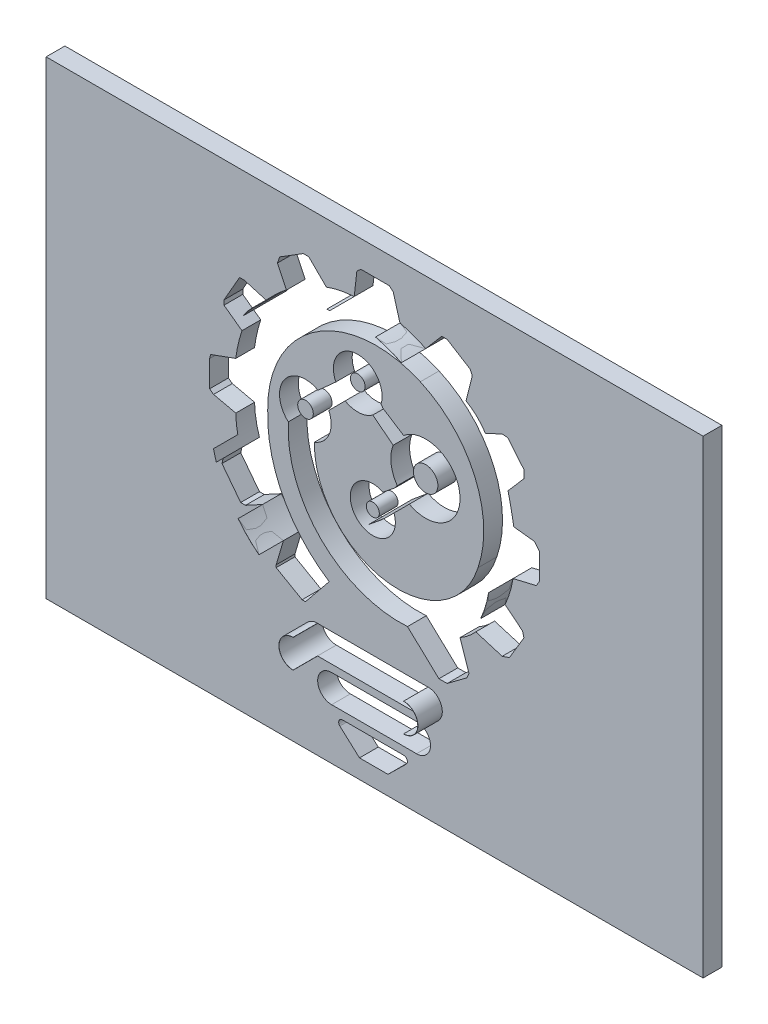
SolidWorks part; units mm, degrees
ref_plane "Front Plane" through (0, 0, 0) normal (0, 0, 1) x (1, 0, 0)
ref_plane "Top Plane" through (0, 0, 0) normal (0, 1, 0) x (1, 0, 0)
ref_plane "Right Plane" through (0, 0, 0) normal (1, 0, 0) x (0, 0, -1)
sketch "Sketch1" plane through (0, 0, 0) normal (0, 0, 1) x (1, 0, 0)
  line L0 (30.4571, 56.7891) -> (92.9051, 56.7891) construction
  line L1 (36.6127, 46.336) -> (66.0639, 46.336) construction
  line L8 (36.6127, 50.1281) -> (66.0639, 50.1281)
  line L11 (36.6127, 42.5438) -> (66.0639, 42.5438)
  line L12 (40.3711, 36.92) -> (62.9922, 36.92) construction
  line L15 (40.3711, 40.6319) -> (62.9922, 40.6319)
  line L16 (40.3711, 33.2082) -> (62.9922, 33.2082)
  line L17 (43.2916, 31.1455) -> (59.5488, 31.1455)
  line L20 (47.7936, 24.6426) -> (55.3803, 24.6426)
  line L21 (60.2553, 29.4313) -> (55.3803, 24.6426)
  line L22 (42.5548, 29.3665) -> (47.7936, 24.6426)
  line L23 (54.0424, 89.0572) -> (57.3383, 91.7453)
  line L24 (56.7754, 86.2384) -> (60.0907, 88.9424)
  line L25 (61.0672, 89.823) -> (60.0907, 88.9424)
  line L26 (57.8581, 92.482) -> (57.3383, 91.7453)
  line L27 (56.7753, 101.2636) -> (51.3382, 105.5029)
  line L28 (59.5486, 104.8905) -> (54.0422, 108.4233)
  line L29 (54.0422, 108.4233) -> (53.5429, 109.1547)
  line L30 (41.4931, 108.2048) -> (36.7513, 103.9283)
  line L31 (43.9752, 105.087) -> (39.6194, 100.7312)
  line L32 (60.5789, 61.3321) -> (68.9548, 53.4849)
  line L33 (71.1414, 53.4849) -> (76.4211, 57.4313)
  line L34 (76.4211, 57.4313) -> (76.9544, 58.7112)
  line L35 (68.9548, 53.4849) -> (71.1414, 53.4849)
  line L36 (76.9544, 58.7112) -> (74.5729, 65.7776)
  line L38 (78.7757, 69.2055) -> (85.8154, 67.0935)
  line L39 (85.8154, 67.0935) -> (87.7229, 67.7364)
  line L40 (87.7229, 67.7364) -> (91.598, 74.2278)
  line L41 (91.598, 74.2278) -> (91.2456, 75.6243)
  line L42 (91.2456, 75.6243) -> (86.565, 79.3976)
  line L44 (88.6833, 86.4585) -> (94.9099, 87.9467)
  line L45 (94.9099, 87.9467) -> (95.7671, 89.3827)
  line L46 (95.7671, 89.3827) -> (95.7671, 96.2119)
  line L47 (95.7671, 96.2119) -> (94.413, 97.8721)
  line L48 (94.413, 97.8721) -> (88.9053, 98.5005)
  line L50 (87.3603, 106.0456) -> (91.6591, 111.0252)
  line L51 (91.6591, 111.0252) -> (91.6591, 112.9758)
  line L52 (91.6591, 112.9758) -> (87.3603, 118.2186)
  line L53 (87.3603, 118.2186) -> (85.8154, 118.3949)
  line L54 (85.8154, 118.3949) -> (81.6957, 116.4107)
  line L55 (81.6957, 116.4107) -> (81.3263, 116.3111)
  line L56 (76.183, 121.1698) -> (77.8389, 127.8606)
  line L57 (77.8389, 127.8606) -> (77.2534, 129.0763)
  line L58 (77.2534, 129.0763) -> (71.1414, 132.8624)
  line L59 (71.1414, 132.8624) -> (69.7035, 132.8624)
  line L60 (69.7035, 132.8624) -> (65.4214, 127.8606)
  line L62 (58.5608, 130.3615) -> (56.7753, 136.6375)
  line L63 (56.7753, 136.6375) -> (55.7168, 137.5437)
  line L64 (55.7168, 137.5437) -> (48.205, 137.5437)
  line L65 (48.205, 137.5437) -> (47.0998, 136.6375)
  line L66 (47.0998, 136.6375) -> (46.3837, 130.3615)
  line L68 (38.9609, 128.8416) -> (34.2686, 133.4995)
  line L69 (34.2686, 133.4995) -> (32.8354, 133.4995)
  line L70 (32.8354, 133.4995) -> (26.5591, 129.6015)
  line L71 (26.5591, 129.6015) -> (25.9244, 127.8606)
  line L72 (25.9244, 127.8606) -> (28.3434, 122.8381)
  line L74 (23.3503, 117.6686) -> (17.1161, 119.5092)
  line L75 (17.1161, 119.5092) -> (15.8505, 119.5092)
  line L76 (15.8505, 119.5092) -> (11.7019, 112.2544)
  line L77 (11.7019, 112.2544) -> (11.7019, 111.0252)
  line L78 (11.7019, 111.0252) -> (16.4833, 107.5433)
  line L80 (14.8364, 100.3097) -> (8.1201, 97.8723)
  line L81 (8.1201, 97.8723) -> (7.8723, 96.7838)
  line L82 (7.8723, 96.7838) -> (7.8723, 89.823)
  line L83 (7.8723, 89.823) -> (8.924, 89.0572)
  line L84 (8.924, 89.0572) -> (14.8364, 87.7111)
  line L86 (16.1477, 80.2776) -> (11.4783, 75.6082)
  line L87 (11.4783, 75.6082) -> (11.164, 74.2278)
  line L88 (11.164, 74.2278) -> (16.1477, 67.7364)
  line L89 (16.1477, 67.7364) -> (17.4483, 67.7364)
  line L90 (17.4483, 67.7364) -> (21.968, 70.1863)
  line L92 (27.5295, 64.6248) -> (25.6004, 58.0911)
  line L93 (25.6004, 58.0911) -> (25.6004, 57.4313)
  line L94 (25.6004, 57.4313) -> (32.5018, 53.4849)
  line L95 (32.5018, 53.4849) -> (33.4122, 53.4849)
  line L96 (33.4122, 53.4849) -> (39.7262, 61.2639)
  arc A4 (36.6127, 50.1281) -> (36.6127, 42.5438) centre (36.6127, 46.336) ccw
  arc A5 (66.0639, 42.5438) -> (66.0639, 50.1281) centre (66.0639, 46.336) ccw
  arc A8 (40.3711, 40.6319) -> (40.3711, 33.2082) centre (40.3711, 36.92) ccw
  arc A9 (62.9922, 33.2082) -> (62.9922, 40.6319) centre (62.9922, 36.92) ccw
  arc A12 (60.2553, 29.4313) -> (59.5488, 31.1455) centre (59.5542, 30.145) ccw
  arc A13 (43.2916, 31.1455) -> (42.5548, 29.3665) centre (43.2916, 30.1034) ccw
  circle A14 centre (51.3383, 83.7011) radius 1.7357
  arc A16 (54.0424, 89.0572) -> (56.7754, 86.2384) centre (51.3383, 83.7011) ccw
  circle A17 centre (65.4214, 97.8721) radius 3.2539
  arc A18 (59.5486, 104.8905) -> (61.0672, 89.823) centre (65.4214, 97.8721) cw
  arc A19 (56.7753, 101.2636) -> (57.8581, 92.482) centre (65.4214, 97.8721) ccw
  circle A20 centre (47.3331, 111.0252) radius 1.9632
  arc A21 (53.5429, 109.1547) -> (41.4931, 108.2048) centre (47.3331, 111.0252) ccw
  arc A22 (51.3382, 105.5029) -> (43.9752, 105.087) centre (47.3331, 111.0252) cw
  circle A23 centre (33.4122, 97.8723) radius 2.0772
  arc A24 (36.7513, 103.9283) -> (28.8345, 92.6889) centre (33.4122, 97.8723) ccw
  arc A25 (39.6194, 100.7312) -> (35.7806, 91.462) centre (33.4122, 97.8723) cw
  arc A26 (28.8345, 92.6889) -> (60.5789, 61.3321) centre (58.5608, 91.0359) ccw
  arc A27 (35.7806, 91.462) -> (79.3675, 84.2956) centre (58.0912, 91.0243) ccw
  arc A28 (79.3675, 84.2956) -> (63.999, 119.5092) centre (52.423, 93.4965) ccw
  arc A29 (63.999, 119.5092) -> (23.3503, 92.7292) centre (52.2487, 93.1048) ccw
  arc A30 (39.7262, 61.2639) -> (23.3503, 92.7292) centre (59.3064, 91.4483) cw
  arc A33 (16.4833, 107.5433) -> (14.8364, 100.3097) centre (52.4804, 95.5437) ccw
  spline S0 degree 2 poles (14.8364, 87.7111) (14.97, 83.7216) (16.1477, 80.2776) knots 0 0 0 1 1 1
  spline S1 degree 2 poles (27.5295, 64.6248) (24.5135, 66.8639) (21.968, 70.1863) knots 0 0 0 1 1 1
  spline S2 degree 2 poles (28.3434, 122.8381) (25.0832, 120.5414) (23.3503, 117.6686) knots 0 0 0 1 1 1
  spline S3 degree 2 poles (46.3837, 130.3615) (43.2077, 130.1934) (38.9609, 128.8416) knots 0 0 0 1 1 1
  spline S4 degree 2 poles (65.4214, 127.8606) (62.7623, 129.3468) (58.5608, 130.3615) knots 0 0 0 1 1 1
  spline S5 degree 2 poles (76.183, 121.1698) (79.2538, 119.4133) (81.3263, 116.3111) knots 0 0 0 1 1 1
  spline S6 degree 1 poles (87.3603, 106.0456) (88.9053, 98.5005) knots 0 0 1 1
  spline S7 degree 2 poles (88.6833, 86.4585) (88.1006, 82.7484) (86.565, 79.3976) knots 0 0 0 1 1 1
  spline S8 degree 2 poles (78.7757, 69.2055) (76.889, 67.188) (74.5729, 65.7776) knots 0 0 0 1 1 1
  point P4 (51.3383, 46.336)
  point P12 (51.6817, 36.92)
extrude "Boss-Extrude1" add sketch "Sketch1" along normal blind 10
sketch "Sketch2" plane through (0, 0, 0) normal (0, 0, -1) x (-1, 0, 0)
  line L1 (-54.14, 86.5559) -> (-58.8145, 90.3685)
  line L2 (-58.8145, 90.3685) -> (-60.3896, 92.6007)
  line L3 (-59.3021, 101.8295) -> (-51.2009, 108.146)
  line L4 (-43.8018, 107.742) -> (-37.0804, 101.0206)
  line L5 (-36.8123, 60.8475) -> (-32.6415, 55.7089)
  line L6 (-32.6415, 55.7089) -> (-32.6415, 55.7089)
  line L7 (-32.6415, 55.7089) -> (-27.7999, 58.4775)
  line L8 (-27.7999, 58.4775) -> (-27.7999, 58.4775)
  line L9 (-27.7999, 58.4775) -> (-29.8561, 65.442)
  line L10 (-22.5558, 72.7799) -> (-17.077, 69.8101)
  line L11 (-17.077, 69.8101) -> (-17.077, 69.8101)
  line L12 (-17.077, 69.8101) -> (-13.3557, 74.6573)
  line L13 (-13.3557, 74.6573) -> (-13.3557, 74.6573)
  line L14 (-13.3557, 74.6573) -> (-18.4724, 79.7739)
  line L15 (-16.8248, 89.3096) -> (-9.8723, 90.8925)
  line L16 (-9.8723, 90.8925) -> (-9.8723, 90.8925)
  line L17 (-9.8723, 90.8925) -> (-9.8723, 96.3806)
  line L18 (-9.8723, 96.3806) -> (-9.8723, 96.3806)
  line L19 (-9.8723, 96.3806) -> (-16.6887, 98.8543)
  line L20 (-18.8683, 108.2807) -> (-13.8311, 111.9488)
  line L21 (-13.8311, 111.9488) -> (-13.8311, 111.9488)
  line L22 (-13.8311, 111.9488) -> (-16.9842, 117.4628)
  line L23 (-16.9842, 117.4628) -> (-16.9842, 117.4628)
  line L24 (-16.9842, 117.4628) -> (-24.3628, 115.2843)
  line L25 (-30.9081, 122.1222) -> (-28.0924, 127.9683)
  line L26 (-28.0924, 127.9683) -> (-28.2014, 128.2672)
  line L27 (-28.2014, 128.2672) -> (-33.4059, 131.4995)
  line L28 (-33.4059, 131.4995) -> (-33.4444, 131.4995)
  line L29 (-33.4444, 131.4995) -> (-38.424, 126.5564)
  line L30 (-48.1674, 128.3526) -> (-48.988, 135.5437)
  line L31 (-48.988, 135.5437) -> (-48.988, 135.5437)
  line L32 (-48.988, 135.5437) -> (-54.9776, 135.5437)
  line L33 (-54.9776, 135.5437) -> (-55.0166, 135.5103)
  line L34 (-55.0166, 135.5103) -> (-56.9612, 128.6751)
  line L35 (-65.8037, 125.2318) -> (-70.6061, 130.8413)
  line L36 (-70.6061, 130.8413) -> (-70.6061, 130.8413)
  line L37 (-70.6061, 130.8413) -> (-75.7045, 127.6831)
  line L38 (-75.7045, 127.6831) -> (-75.7244, 127.6418)
  line L39 (-75.7244, 127.6418) -> (-73.8578, 120.0996)
  line L40 (-80.3979, 113.9894) -> (-82.3959, 114.5281)
  line L41 (-82.3959, 114.5281) -> (-86.1627, 116.3423)
  line L42 (-86.1627, 116.3423) -> (-86.3279, 116.3234)
  line L43 (-86.3279, 116.3234) -> (-89.6591, 112.2607)
  line L44 (-89.6591, 112.2607) -> (-89.6591, 111.769)
  line L45 (-89.6591, 111.769) -> (-85.2037, 106.608)
  line L46 (-85.2037, 106.608) -> (-87.237, 96.6779)
  line L47 (-87.237, 96.6779) -> (-93.3776, 95.9772)
  line L48 (-93.3776, 95.9772) -> (-93.7671, 95.4997)
  line L49 (-93.7671, 95.4997) -> (-93.7671, 89.9342)
  line L50 (-93.7671, 89.9342) -> (-93.6248, 89.6959)
  line L51 (-93.6248, 89.6959) -> (-86.8806, 88.0839)
  line L52 (-84.0603, 78.8479) -> (-89.4385, 74.5121)
  line L53 (-89.4385, 74.5121) -> (-89.4385, 74.5121)
  line L54 (-89.4385, 74.5121) -> (-86.3843, 69.3958)
  line L55 (-86.3843, 69.3958) -> (-85.7801, 69.1922)
  line L56 (-85.7801, 69.1922) -> (-78.1209, 71.49)
  line L57 (-72.1441, 66.722) -> (-74.8187, 58.7857)
  line L58 (-74.8187, 58.7857) -> (-74.7854, 58.7056)
  line L59 (-74.7854, 58.7056) -> (-70.4765, 55.4849)
  line L60 (-70.4765, 55.4849) -> (-69.7453, 55.4849)
  line L61 (-69.7453, 55.4849) -> (-61.2981, 63.3988)
  line L62 (-36.8826, 101.3536) -> (-44.1277, 107.8876)
  line L63 (-51.2885, 108.91) -> (-52.6198, 106.9596)
  line L64 (-52.6198, 106.9596) -> (-59.8316, 102.3327)
  line L65 (-60.8803, 92.3476) -> (-58.7881, 90.4609)
  line L66 (-58.7881, 90.4609) -> (-54.0759, 86.6175)
  line L67 (-54.0424, 89.0572) -> (-57.3383, 91.7453)
  line L68 (-57.3383, 91.7453) -> (-57.8581, 92.482)
  line L69 (-56.7753, 101.2636) -> (-51.3382, 105.5029)
  line L70 (-43.9752, 105.087) -> (-39.6194, 100.7312)
  line L71 (-39.7262, 61.2639) -> (-33.4122, 53.4849)
  line L72 (-33.4122, 53.4849) -> (-32.5018, 53.4849)
  line L73 (-32.5018, 53.4849) -> (-25.6004, 57.4313)
  line L74 (-25.6004, 57.4313) -> (-25.6004, 58.0911)
  line L75 (-25.6004, 58.0911) -> (-27.5295, 64.6248)
  line L76 (-21.968, 70.1863) -> (-17.4483, 67.7364)
  line L77 (-17.4483, 67.7364) -> (-16.1477, 67.7364)
  line L78 (-16.1477, 67.7364) -> (-11.164, 74.2278)
  line L79 (-11.164, 74.2278) -> (-11.4783, 75.6082)
  line L80 (-11.4783, 75.6082) -> (-16.1477, 80.2776)
  line L81 (-14.8364, 87.7111) -> (-8.924, 89.0572)
  line L82 (-8.924, 89.0572) -> (-7.8723, 89.823)
  line L83 (-7.8723, 89.823) -> (-7.8723, 96.7838)
  line L84 (-7.8723, 96.7838) -> (-8.1201, 97.8723)
  line L85 (-8.1201, 97.8723) -> (-14.8364, 100.3097)
  line L86 (-16.4833, 107.5433) -> (-11.7019, 111.0252)
  line L87 (-11.7019, 111.0252) -> (-11.7019, 112.2544)
  line L88 (-11.7019, 112.2544) -> (-15.8505, 119.5092)
  line L89 (-15.8505, 119.5092) -> (-17.1161, 119.5092)
  line L90 (-17.1161, 119.5092) -> (-23.3503, 117.6686)
  line L91 (-28.3434, 122.8381) -> (-25.9244, 127.8606)
  line L92 (-25.9244, 127.8606) -> (-26.5591, 129.6015)
  line L93 (-26.5591, 129.6015) -> (-32.8354, 133.4995)
  line L94 (-32.8354, 133.4995) -> (-34.2686, 133.4995)
  line L95 (-34.2686, 133.4995) -> (-38.9609, 128.8416)
  line L96 (-46.3837, 130.3615) -> (-47.0998, 136.6375)
  line L97 (-47.0998, 136.6375) -> (-48.205, 137.5437)
  line L98 (-48.205, 137.5437) -> (-55.7168, 137.5437)
  line L99 (-55.7168, 137.5437) -> (-56.7753, 136.6375)
  line L100 (-56.7753, 136.6375) -> (-58.5608, 130.3615)
  line L101 (-65.4214, 127.8606) -> (-69.7035, 132.8624)
  line L102 (-69.7035, 132.8624) -> (-71.1414, 132.8624)
  line L103 (-71.1414, 132.8624) -> (-77.2534, 129.0763)
  line L104 (-77.2534, 129.0763) -> (-77.8389, 127.8606)
  line L105 (-77.8389, 127.8606) -> (-76.183, 121.1698)
  line L106 (-81.3263, 116.3111) -> (-81.6957, 116.4107)
  line L107 (-81.6957, 116.4107) -> (-85.8154, 118.3949)
  line L108 (-85.8154, 118.3949) -> (-87.3603, 118.2186)
  line L109 (-87.3603, 118.2186) -> (-91.6591, 112.9758)
  line L110 (-91.6591, 112.9758) -> (-91.6591, 111.0252)
  line L111 (-91.6591, 111.0252) -> (-87.3603, 106.0456)
  line L112 (-87.3603, 106.0456) -> (-88.9053, 98.5005)
  line L113 (-88.9053, 98.5005) -> (-94.413, 97.8721)
  line L114 (-94.413, 97.8721) -> (-95.7671, 96.2119)
  line L115 (-95.7671, 96.2119) -> (-95.7671, 89.3827)
  line L116 (-95.7671, 89.3827) -> (-94.9099, 87.9467)
  line L117 (-94.9099, 87.9467) -> (-88.6833, 86.4585)
  line L118 (-86.565, 79.3976) -> (-91.2456, 75.6243)
  line L119 (-91.2456, 75.6243) -> (-91.598, 74.2278)
  line L120 (-91.598, 74.2278) -> (-87.7229, 67.7364)
  line L121 (-87.7229, 67.7364) -> (-85.8154, 67.0935)
  line L122 (-85.8154, 67.0935) -> (-78.7757, 69.2055)
  line L123 (-74.5729, 65.7776) -> (-76.9544, 58.7112)
  line L124 (-76.9544, 58.7112) -> (-76.4211, 57.4313)
  line L125 (-76.4211, 57.4313) -> (-71.1414, 53.4849)
  line L126 (-71.1414, 53.4849) -> (-68.9548, 53.4849)
  line L127 (-68.9548, 53.4849) -> (-60.5789, 61.3321)
  line L128 (-36.7513, 103.9283) -> (-41.4931, 108.2048)
  line L129 (-53.5429, 109.1547) -> (-54.0422, 108.4233)
  line L130 (-54.0422, 108.4233) -> (-59.5486, 104.8905)
  line L131 (-61.0672, 89.823) -> (-60.0907, 88.9424)
  line L132 (-60.0907, 88.9424) -> (-56.7754, 86.2384)
  line L133 (-54.0424, 89.0572) -> (-57.3383, 91.7453)
  line L134 (-57.3383, 91.7453) -> (-57.8581, 92.482)
  line L135 (-56.7753, 101.2636) -> (-51.3382, 105.5029)
  line L136 (-43.9752, 105.087) -> (-39.6194, 100.7312)
  line L137 (-39.7262, 61.2639) -> (-33.4122, 53.4849)
  line L138 (-33.4122, 53.4849) -> (-32.5018, 53.4849)
  line L139 (-32.5018, 53.4849) -> (-25.6004, 57.4313)
  line L140 (-25.6004, 57.4313) -> (-25.6004, 58.0911)
  line L141 (-25.6004, 58.0911) -> (-27.5295, 64.6248)
  line L142 (-21.968, 70.1863) -> (-17.4483, 67.7364)
  line L143 (-17.4483, 67.7364) -> (-16.1477, 67.7364)
  line L144 (-16.1477, 67.7364) -> (-11.164, 74.2278)
  line L145 (-11.164, 74.2278) -> (-11.4783, 75.6082)
  line L146 (-11.4783, 75.6082) -> (-16.1477, 80.2776)
  line L147 (-14.8364, 87.7111) -> (-8.924, 89.0572)
  line L148 (-8.924, 89.0572) -> (-7.8723, 89.823)
  line L149 (-7.8723, 89.823) -> (-7.8723, 96.7838)
  line L150 (-7.8723, 96.7838) -> (-8.1201, 97.8723)
  line L151 (-8.1201, 97.8723) -> (-14.8364, 100.3097)
  line L152 (-16.4833, 107.5433) -> (-11.7019, 111.0252)
  line L153 (-11.7019, 111.0252) -> (-11.7019, 112.2544)
  line L154 (-11.7019, 112.2544) -> (-15.8505, 119.5092)
  line L155 (-15.8505, 119.5092) -> (-17.1161, 119.5092)
  line L156 (-17.1161, 119.5092) -> (-23.3503, 117.6686)
  line L157 (-28.3434, 122.8381) -> (-25.9244, 127.8606)
  line L158 (-25.9244, 127.8606) -> (-26.5591, 129.6015)
  line L159 (-26.5591, 129.6015) -> (-32.8354, 133.4995)
  line L160 (-32.8354, 133.4995) -> (-34.2686, 133.4995)
  line L161 (-34.2686, 133.4995) -> (-38.9609, 128.8416)
  line L162 (-46.3837, 130.3615) -> (-47.0998, 136.6375)
  line L163 (-47.0998, 136.6375) -> (-48.205, 137.5437)
  line L164 (-48.205, 137.5437) -> (-55.7168, 137.5437)
  line L165 (-55.7168, 137.5437) -> (-56.7753, 136.6375)
  line L166 (-56.7753, 136.6375) -> (-58.5608, 130.3615)
  line L167 (-65.4214, 127.8606) -> (-69.7035, 132.8624)
  line L168 (-69.7035, 132.8624) -> (-71.1414, 132.8624)
  line L169 (-71.1414, 132.8624) -> (-77.2534, 129.0763)
  line L170 (-77.2534, 129.0763) -> (-77.8389, 127.8606)
  line L171 (-77.8389, 127.8606) -> (-76.183, 121.1698)
  line L172 (-81.3263, 116.3111) -> (-81.6957, 116.4107)
  line L173 (-81.6957, 116.4107) -> (-85.8154, 118.3949)
  line L174 (-85.8154, 118.3949) -> (-87.3603, 118.2186)
  line L175 (-87.3603, 118.2186) -> (-91.6591, 112.9758)
  line L176 (-91.6591, 112.9758) -> (-91.6591, 111.0252)
  line L177 (-91.6591, 111.0252) -> (-87.3603, 106.0456)
  line L178 (-87.3603, 106.0456) -> (-88.9053, 98.5005)
  line L179 (-88.9053, 98.5005) -> (-94.413, 97.8721)
  line L180 (-94.413, 97.8721) -> (-95.7671, 96.2119)
  line L181 (-95.7671, 96.2119) -> (-95.7671, 89.3827)
  line L182 (-95.7671, 89.3827) -> (-94.9099, 87.9467)
  line L183 (-94.9099, 87.9467) -> (-88.6833, 86.4585)
  line L184 (-86.565, 79.3976) -> (-91.2456, 75.6243)
  line L185 (-91.2456, 75.6243) -> (-91.598, 74.2278)
  line L186 (-91.598, 74.2278) -> (-87.7229, 67.7364)
  line L187 (-87.7229, 67.7364) -> (-85.8154, 67.0935)
  line L188 (-85.8154, 67.0935) -> (-78.7757, 69.2055)
  line L189 (-74.5729, 65.7776) -> (-76.9544, 58.7112)
  line L190 (-76.9544, 58.7112) -> (-76.4211, 57.4313)
  line L191 (-76.4211, 57.4313) -> (-71.1414, 53.4849)
  line L192 (-71.1414, 53.4849) -> (-68.9548, 53.4849)
  line L193 (-68.9548, 53.4849) -> (-60.5789, 61.3321)
  line L194 (-36.7513, 103.9283) -> (-41.4931, 108.2048)
  line L195 (-53.5429, 109.1547) -> (-54.0422, 108.4233)
  line L196 (-54.0422, 108.4233) -> (-59.5486, 104.8905)
  line L197 (-61.0672, 89.823) -> (-60.0907, 88.9424)
  line L198 (-60.0907, 88.9424) -> (-56.7754, 86.2384)
  arc A0 (-54.0759, 86.6175) -> (-54.14, 86.5559) centre (-51.3383, 83.7011) ccw
  arc A1 (-60.3896, 92.6007) -> (-59.3021, 101.8295) centre (-65.4214, 97.8721) ccw
  arc A2 (-51.2009, 108.146) -> (-43.8018, 107.742) centre (-47.3331, 111.0252) ccw
  arc A3 (-37.0804, 101.0206) -> (-33.8616, 93.0594) centre (-33.4122, 97.8723) ccw
  arc A4 (-81.2676, 83.6708) -> (-33.8616, 93.0594) centre (-58.0912, 91.0243) ccw
  arc A5 (-64.8122, 121.3364) -> (-81.2676, 83.6708) centre (-52.423, 93.4965) ccw
  arc A6 (-21.3499, 92.752) -> (-64.8122, 121.3364) centre (-52.2487, 93.1048) ccw
  arc A7 (-36.8123, 60.8475) -> (-21.3499, 92.752) centre (-59.3064, 91.4483) ccw
  arc A8 (-16.6887, 98.8543) -> (-18.8683, 108.2807) centre (-52.4804, 95.5437) ccw
  arc A9 (-61.2981, 63.3988) -> (-30.911, 93.6408) centre (-58.5608, 91.0359) ccw
  arc A10 (-30.911, 93.6408) -> (-36.8826, 101.3536) centre (-33.4122, 97.8723) ccw
  arc A11 (-44.1277, 107.8876) -> (-51.2885, 108.91) centre (-47.3331, 111.0252) ccw
  arc A12 (-59.8316, 102.3327) -> (-60.8803, 92.3476) centre (-65.4214, 97.8721) ccw
  arc A13 (-56.7754, 86.2384) -> (-54.0424, 89.0572) centre (-51.3383, 83.7011) ccw
  arc A14 (-57.8581, 92.482) -> (-56.7753, 101.2636) centre (-65.4214, 97.8721) ccw
  arc A15 (-51.3382, 105.5029) -> (-43.9752, 105.087) centre (-47.3331, 111.0252) ccw
  arc A16 (-39.6194, 100.7312) -> (-35.7806, 91.462) centre (-33.4122, 97.8723) ccw
  arc A17 (-79.3675, 84.2956) -> (-35.7806, 91.462) centre (-58.0912, 91.0243) ccw
  arc A18 (-63.999, 119.5092) -> (-79.3675, 84.2956) centre (-52.423, 93.4965) ccw
  arc A19 (-23.3503, 92.7292) -> (-63.999, 119.5092) centre (-52.2487, 93.1048) ccw
  arc A20 (-39.7262, 61.2639) -> (-23.3503, 92.7292) centre (-59.3064, 91.4483) ccw
  arc A21 (-14.8364, 100.3097) -> (-16.4833, 107.5433) centre (-52.4804, 95.5437) ccw
  arc A22 (-60.5789, 61.3321) -> (-28.8345, 92.6889) centre (-58.5608, 91.0359) ccw
  arc A23 (-28.8345, 92.6889) -> (-36.7513, 103.9283) centre (-33.4122, 97.8723) ccw
  arc A24 (-41.4931, 108.2048) -> (-53.5429, 109.1547) centre (-47.3331, 111.0252) ccw
  arc A25 (-59.5486, 104.8905) -> (-61.0672, 89.823) centre (-65.4214, 97.8721) ccw
  arc A26 (-56.7754, 86.2384) -> (-54.0424, 89.0572) centre (-51.3383, 83.7011) ccw
  arc A27 (-57.8581, 92.482) -> (-56.7753, 101.2636) centre (-65.4214, 97.8721) ccw
  arc A28 (-51.3382, 105.5029) -> (-43.9752, 105.087) centre (-47.3331, 111.0252) ccw
  arc A29 (-39.6194, 100.7312) -> (-35.7806, 91.462) centre (-33.4122, 97.8723) ccw
  arc A30 (-79.3675, 84.2956) -> (-35.7806, 91.462) centre (-58.0912, 91.0243) ccw
  arc A31 (-63.999, 119.5092) -> (-79.3675, 84.2956) centre (-52.423, 93.4965) ccw
  arc A32 (-23.3503, 92.7292) -> (-63.999, 119.5092) centre (-52.2487, 93.1048) ccw
  arc A33 (-39.7262, 61.2639) -> (-23.3503, 92.7292) centre (-59.3064, 91.4483) ccw
  arc A34 (-14.8364, 100.3097) -> (-16.4833, 107.5433) centre (-52.4804, 95.5437) ccw
  arc A35 (-60.5789, 61.3321) -> (-28.8345, 92.6889) centre (-58.5608, 91.0359) ccw
  arc A36 (-28.8345, 92.6889) -> (-36.7513, 103.9283) centre (-33.4122, 97.8723) ccw
  arc A37 (-41.4931, 108.2048) -> (-53.5429, 109.1547) centre (-47.3331, 111.0252) ccw
  arc A38 (-59.5486, 104.8905) -> (-61.0672, 89.823) centre (-65.4214, 97.8721) ccw
  parabola Q8 (-27.5295, 64.6248) -> (-21.968, 70.1863) focus (-36.6411, 72.3496) apex (-32.1285, 61.957)
  parabola Q9 (-16.1477, 80.2776) -> (-14.8364, 87.7111) focus (-27.2163, 82.2633) apex (-17.4778, 77.1751)
  parabola Q10 (-23.3503, 117.6686) -> (-28.3434, 122.8381) focus (-28.5124, 113.0969) apex (-22.2722, 115.4509)
  parabola Q11 (-38.9609, 128.8416) -> (-46.3837, 130.3615) focus (-51.1069, 126.1376) apex (-53.2201, 128.4735)
  parabola Q12 (-58.5608, 130.3615) -> (-65.4214, 127.8606) focus (-66.8713, 122.2923) apex (-69.7381, 123.1689)
  parabola Q13 (-76.183, 121.1698) -> (-81.3263, 116.3111) focus (-73.2684, 114.293) apex (-77.656, 120.2074)
  parabola Q14 (-88.6833, 86.4585) -> (-86.565, 79.3976) focus (-74.8514, 85.7796) apex (-87.2732, 81.0955)
  parabola Q15 (-78.7757, 69.2055) -> (-74.5729, 65.7776) focus (-70.0201, 74.5575) apex (-75.7041, 66.5208)
  parabola Q16 (-27.5295, 64.6248) -> (-21.968, 70.1863) focus (-36.6411, 72.3496) apex (-32.1285, 61.957)
  parabola Q17 (-16.1477, 80.2776) -> (-14.8364, 87.7111) focus (-27.2163, 82.2633) apex (-17.4778, 77.1751)
  parabola Q18 (-23.3503, 117.6686) -> (-28.3434, 122.8381) focus (-28.5124, 113.0969) apex (-22.2722, 115.4509)
  parabola Q19 (-38.9609, 128.8416) -> (-46.3837, 130.3615) focus (-51.1069, 126.1376) apex (-53.2201, 128.4735)
  parabola Q20 (-58.5608, 130.3615) -> (-65.4214, 127.8606) focus (-66.8713, 122.2923) apex (-69.7381, 123.1689)
  parabola Q21 (-76.183, 121.1698) -> (-81.3263, 116.3111) focus (-73.2684, 114.293) apex (-77.656, 120.2074)
  parabola Q22 (-88.6833, 86.4585) -> (-86.565, 79.3976) focus (-74.8514, 85.7796) apex (-87.2732, 81.0955)
  parabola Q23 (-78.7757, 69.2055) -> (-74.5729, 65.7776) focus (-70.0201, 74.5575) apex (-75.7041, 66.5208)
  spline S0 degree 1 poles (-29.8561, 65.442) (-22.5558, 72.7799) knots 0 0 1 1 construction
  spline S1 degree 1 poles (-18.4724, 79.7739) (-16.8248, 89.3096) knots 0 0 1 1 construction
  spline S2 degree 1 poles (-24.3628, 115.2843) (-30.9081, 122.1222) knots 0 0 1 1 construction
  spline S3 degree 1 poles (-38.424, 126.5564) (-48.1674, 128.3526) knots 0 0 1 1 construction
  spline S4 degree 1 poles (-56.9612, 128.6751) (-65.8037, 125.2318) knots 0 0 1 1 construction
  spline S5 degree 1 poles (-73.8578, 120.0996) (-80.3979, 113.9894) knots 0 0 1 1 construction
  spline S6 degree 1 poles (-86.8806, 88.0839) (-84.0603, 78.8479) knots 0 0 1 1 construction
  spline S7 degree 1 poles (-78.1209, 71.49) (-72.1441, 66.722) knots 0 0 1 1 construction
  spline S8 degree 3 poles (-29.8561, 65.442) (-29.1755, 65.884) (-27.8791, 66.8318) (-26.0024, 68.5312) (-24.5199, 70.1696) (-23.3838, 71.612) (-22.8245, 72.3896) (-22.5558, 72.7799) knots 0.500282 0.500282 0.500282 0.500282 0.500475 0.500667 0.500859 0.500955 0.501051 0.501051 0.501051 0.501051
  spline S9 degree 3 poles (-18.4724, 79.7739) (-18.1809, 80.4842) (-17.6821, 81.9251) (-17.1525, 84.2374) (-16.9031, 86.281) (-16.8191, 87.9836) (-16.8164, 88.8707) (-16.8248, 89.3096) knots 0.500153 0.500153 0.500153 0.500153 0.500341 0.50053 0.500718 0.500812 0.500906 0.500906 0.500906 0.500906
  spline S10 degree 3 poles (-24.3628, 115.2843) (-24.6467, 115.9337) (-25.3222, 117.1593) (-26.735, 118.9215) (-28.2635, 120.3079) (-29.6944, 121.3595) (-30.5042, 121.879) (-30.9081, 122.1222) knots 0.500066 0.500066 0.500066 0.500066 0.500305 0.500543 0.500781 0.5009 0.501019 0.501019 0.501019 0.501019
  spline S11 degree 3 poles (-38.424, 126.5564) (-38.9237, 126.7287) (-39.9513, 127.0654) (-41.8435, 127.6142) (-44.0285, 128.1106) (-45.9197, 128.35) (-47.2723, 128.3963) (-47.8625, 128.3756) (-48.1674, 128.3526) knots 0.498389 0.498389 0.498389 0.498389 0.498504 0.498619 0.49885 0.49908 0.499196 0.499311 0.499311 0.499311 0.499311
  spline S12 degree 3 poles (-56.9612, 128.6751) (-57.464, 128.5668) (-58.4903, 128.3285) (-60.3332, 127.8285) (-62.3772, 127.1332) (-64.0252, 126.3705) (-65.1246, 125.7212) (-65.5766, 125.4058) (-65.8037, 125.2318) knots 0.498448 0.498448 0.498448 0.498448 0.498565 0.498681 0.498915 0.499148 0.499264 0.499381 0.499381 0.499381 0.499381
  spline S13 degree 3 poles (-73.8578, 120.0996) (-74.5416, 119.8034) (-75.8747, 119.0902) (-77.5953, 117.7419) (-78.8646, 116.3448) (-79.7724, 115.063) (-80.2001, 114.3485) (-80.3979, 113.9894) knots 0.499683 0.499683 0.499683 0.499683 0.499917 0.500152 0.500386 0.500504 0.500621 0.500621 0.500621 0.500621
  spline S14 degree 3 poles (-86.8806, 88.0839) (-86.7933, 87.2651) (-86.5412, 85.622) (-85.9467, 83.2789) (-85.1338, 81.0177) (-84.4403, 79.5575) (-84.0603, 78.8479) knots 0.499526 0.499526 0.499526 0.499526 0.499705 0.499883 0.500062 0.50024 0.50024 0.50024 0.50024
  spline S15 degree 3 poles (-78.1209, 71.49) (-77.7049, 70.985) (-76.8135, 70.0072) (-75.3833, 68.7382) (-73.837, 67.6345) (-72.7167, 67.0052) (-72.1441, 66.722) knots 0.499572 0.499572 0.499572 0.499572 0.499741 0.49991 0.500078 0.500247 0.500247 0.500247 0.500247
  dimension "D1" = 0
  dimension "D2" = 2
extrude "Cut-Extrude2" cut sketch "Sketch2" against normal blind 3.5 contours L56 S15 L57 L58 L59 L60 L61 A9 A10 L62 L4 A3 A4 A5 A6 A7 L5 L7 L9 S8 L10 L12 L14 S9 L15 L17 L19 A8 L20 L22 L24 S10 L25 L26 L27 L28 L29 S11 L30 L32 L33 L34 S12 L35 L37 L38 L39 S13 L40 L41 L42
sketch "Sketch3" plane through (0, 0, 3.5) normal (0, 0, -1) x (-1, 0, 0)
  line L0 (-95.7671, 89.3827) -> (-95.7671, 96.2119) construction
  line L1 (35.6779, 144.6308) -> (-139.3221, 144.6308)
  line L2 (35.6779, 144.6308) -> (35.6779, 19.6308)
  line L3 (35.6779, 19.6308) -> (-139.3221, 19.6308)
  line L4 (-139.3221, 144.6308) -> (-139.3221, 19.6308)
  dimension "D1" = 125
  dimension "D2" = 175
  dimension "D3" = 43.555
extrude "Boss-Extrude2" add sketch "Sketch3" along normal blind 5
sketch "Sketch4" plane through (0, 0, 10) normal (0, 0, 1) x (1, 0, 0)
  line L0 (62.9922, 36.92) -> (40.3711, 36.92) construction
  line L2 (95.7671, 96.2119) -> (95.7671, 89.3827)
  line L3 (95.7671, 89.3827) -> (94.9099, 87.9467)
  line L4 (94.9099, 87.9467) -> (88.6833, 86.4585)
  line L5 (95.7671, 96.2119) -> (94.413, 97.8721)
  line L6 (94.413, 97.8721) -> (88.9053, 98.5005)
  line L7 (86.565, 79.3976) -> (91.2456, 75.6243)
  line L8 (91.2456, 75.6243) -> (91.598, 74.2278)
  line L9 (91.598, 74.2278) -> (87.7229, 67.7364)
  line L10 (87.7229, 67.7364) -> (85.8154, 67.0935)
  line L11 (85.8154, 67.0935) -> (78.7757, 69.2055)
  line L12 (74.5729, 65.7776) -> (76.9544, 58.7112)
  line L13 (76.9544, 58.7112) -> (76.4211, 57.4313)
  line L14 (76.4211, 57.4313) -> (71.1414, 53.4849)
  line L15 (71.1414, 53.4849) -> (68.9548, 53.4849)
  line L16 (68.9548, 53.4849) -> (60.5789, 61.3321)
  line L17 (39.7262, 61.2639) -> (33.4122, 53.4849)
  line L18 (33.4122, 53.4849) -> (32.5018, 53.4849)
  line L19 (32.5018, 53.4849) -> (25.6004, 57.4313)
  line L20 (25.6004, 57.4313) -> (25.6004, 58.0911)
  line L21 (25.6004, 58.0911) -> (27.5295, 64.6248)
  line L22 (21.968, 70.1863) -> (17.4483, 67.7364)
  line L23 (17.4483, 67.7364) -> (16.1477, 67.7364)
  line L24 (16.1477, 67.7364) -> (11.164, 74.2278)
  line L25 (11.164, 74.2278) -> (11.4783, 75.6082)
  line L26 (11.4783, 75.6082) -> (16.1477, 80.2776)
  line L27 (14.8364, 87.7111) -> (8.924, 89.0572)
  line L28 (8.924, 89.0572) -> (7.8723, 89.823)
  line L29 (7.8723, 89.823) -> (7.8723, 96.7838)
  line L30 (7.8723, 96.7838) -> (8.1201, 97.8723)
  line L31 (8.1201, 97.8723) -> (14.8364, 100.3097)
  line L33 (11.7019, 111.0252) -> (11.7019, 112.2544)
  line L34 (11.7019, 112.2544) -> (15.8505, 119.5092)
  line L35 (15.8505, 119.5092) -> (17.1161, 119.5092)
  line L36 (17.1161, 119.5092) -> (23.3503, 117.6686)
  line L37 (28.3434, 122.8381) -> (25.9244, 127.8606)
  line L38 (25.9244, 127.8606) -> (26.5591, 129.6015)
  line L39 (26.5591, 129.6015) -> (32.8354, 133.4995)
  line L40 (32.8354, 133.4995) -> (34.2686, 133.4995)
  line L41 (34.2686, 133.4995) -> (38.9609, 128.8416)
  line L42 (46.3837, 130.3615) -> (47.0998, 136.6375)
  line L43 (47.0998, 136.6375) -> (48.205, 137.5437)
  line L44 (48.205, 137.5437) -> (55.7168, 137.5437)
  line L45 (55.7168, 137.5437) -> (56.7753, 136.6375)
  line L46 (56.7753, 136.6375) -> (58.5608, 130.3615)
  line L47 (65.4214, 127.8606) -> (69.7035, 132.8624)
  line L48 (69.7035, 132.8624) -> (71.1414, 132.8624)
  line L49 (71.1414, 132.8624) -> (77.2534, 129.0763)
  line L50 (77.2534, 129.0763) -> (77.8389, 127.8606)
  line L51 (77.8389, 127.8606) -> (76.183, 121.1698)
  line L52 (87.3603, 106.0456) -> (91.6591, 111.0252)
  line L53 (91.6591, 111.0252) -> (91.6591, 112.9758)
  line L54 (91.6591, 112.9758) -> (87.3603, 118.2186)
  line L55 (87.3603, 118.2186) -> (85.8154, 118.3949)
  line L56 (85.8154, 118.3949) -> (81.6957, 116.4107)
  line L57 (81.3263, 116.3111) -> (81.6957, 116.4107)
  line L58 (55.3803, 24.6426) -> (47.7936, 24.6426)
  line L59 (47.7936, 24.6426) -> (42.5548, 29.3665)
  line L60 (43.2916, 31.1455) -> (59.5488, 31.1455)
  line L61 (60.2553, 29.4313) -> (55.3803, 24.6426)
  line L62 (60.0907, 88.9424) -> (61.0672, 89.823) construction
  line L63 (57.3383, 91.7453) -> (57.8581, 92.482) construction
  line L64 (66.0639, 46.3354) -> (36.6127, 46.3354) construction
  line L65 (66.0639, 42.5756) -> (36.6127, 42.5756)
  line L66 (66.0639, 50.0953) -> (36.6127, 50.0953)
  line L68 (62.9922, 33.2049) -> (40.3711, 33.2049)
  line L69 (62.9922, 40.6352) -> (40.3711, 40.6352)
  line L70 (43.9752, 105.087) -> (39.6194, 100.7312) construction
  line L71 (43.9752, 105.087) -> (39.6194, 100.7312)
  line L72 (41.4931, 108.2048) -> (36.7513, 103.9283)
  line L73 (53.5429, 109.1547) -> (54.0422, 108.4233)
  line L74 (54.0422, 108.4233) -> (59.5486, 104.8905)
  line L75 (51.3382, 105.5029) -> (56.7753, 101.2636)
  line L76 (56.7754, 86.2384) -> (61.0672, 89.823)
  line L78 (54.0424, 89.0572) -> (57.3383, 91.7453)
  line L79 (57.8581, 92.482) -> (57.3383, 91.7453)
  line L80 (11.7019, 111.0252) -> (16.4833, 107.5433)
  arc A0 (66.0639, 42.5756) -> (66.0639, 50.0953) centre (66.0639, 46.3354) ccw
  arc A1 (36.6127, 50.0953) -> (36.6127, 42.5756) centre (36.6127, 46.3354) ccw
  arc A4 (62.9922, 33.2049) -> (62.9922, 40.6352) centre (62.9922, 36.92) ccw
  arc A5 (40.3711, 40.6352) -> (40.3711, 33.2049) centre (40.3711, 36.92) ccw
  arc A6 (59.5488, 31.1455) -> (60.2553, 29.4313) centre (59.5488, 30.1428) cw
  arc A8 (42.5548, 29.3665) -> (43.2916, 31.1455) centre (43.2916, 30.1034) cw
  circle A9 centre (33.4122, 97.8723) radius 2.0772
  circle A10 centre (47.3331, 111.0252) radius 1.9632
  circle A11 centre (65.4214, 97.8721) radius 3.2539
  circle A13 centre (51.3383, 83.7011) radius 1.7357
  arc A17 (54.0424, 89.0572) -> (56.7754, 86.2384) centre (51.3383, 83.7011) ccw
  arc A18 (54.0424, 89.0572) -> (56.7754, 86.2384) centre (51.3383, 83.7011) ccw construction
  arc A19 (59.5486, 104.8905) -> (61.0672, 89.823) centre (65.4214, 97.8721) cw
  arc A20 (56.7753, 101.2636) -> (57.8581, 92.482) centre (65.4214, 97.8721) ccw
  arc A21 (56.7753, 101.2636) -> (57.8581, 92.482) centre (65.4214, 97.8721) ccw construction
  arc A22 (56.7753, 101.2636) -> (57.8581, 92.482) centre (65.4214, 97.8721) ccw construction
  arc A23 (53.5429, 109.1547) -> (41.4931, 108.2048) centre (47.3331, 111.0252) ccw
  arc A24 (51.3382, 105.5029) -> (43.9752, 105.087) centre (47.3331, 111.0252) cw
  arc A26 (36.7513, 103.9283) -> (28.8345, 92.6889) centre (33.4122, 97.8723) ccw
  arc A27 (28.8345, 92.6889) -> (60.5789, 61.3321) centre (58.5608, 91.0359) ccw construction
  arc A28 (39.6194, 100.7312) -> (35.7806, 91.462) centre (33.4122, 97.8723) cw
  arc A29 (35.7806, 91.462) -> (39.6194, 100.7312) centre (33.4122, 97.8723) ccw construction
  arc A30 (35.7806, 91.462) -> (39.6194, 100.7312) centre (33.4122, 97.8723) ccw construction
  arc A32 (58.5608, 130.3615) -> (65.4214, 127.8606) centre (50.8878, 98.6518) cw
  arc A33 (76.183, 121.1698) -> (81.3263, 116.3111) centre (68.8026, 108.2053) cw
  arc A34 (87.3603, 106.0456) -> (88.9053, 98.5005) centre (-37.3015, 76.5889) cw
  arc A35 (88.6833, 86.4585) -> (86.565, 79.3976) centre (60.2964, 91.1266) cw
  arc A36 (78.7757, 69.2055) -> (74.5729, 65.7776) centre (66.1629, 80.3796) cw
  arc A37 (46.3837, 130.3615) -> (38.9609, 128.8416) centre (47.9579, 103.7882) ccw
  arc A38 (28.3434, 122.8381) -> (23.3503, 117.6686) centre (38.9914, 107.5573) ccw
  arc A39 (16.4833, 107.5433) -> (14.8364, 100.3097) centre (52.4804, 95.5437) ccw
  arc A40 (14.8364, 87.7111) -> (16.1477, 80.2776) centre (40.0614, 88.3283) ccw
  arc A41 (21.968, 70.1863) -> (27.5295, 64.6248) centre (46.6119, 89.2687) ccw
  arc A42 (35.7806, 91.462) -> (79.3675, 84.2956) centre (58.0912, 91.0243) ccw
  arc A43 (79.3675, 84.2956) -> (63.999, 119.5092) centre (52.423, 93.4965) ccw
  arc A44 (63.999, 119.5092) -> (23.3503, 92.7292) centre (52.2487, 93.1048) ccw
  arc A45 (23.3503, 92.7292) -> (39.7262, 61.2639) centre (59.3064, 91.4483) ccw
  arc A46 (60.5789, 61.3321) -> (28.8345, 92.6889) centre (58.5608, 91.0359) cw
  point P4 (51.6817, 36.92)
  point P165 (51.3383, 46.3354)
extrude "Cut-Extrude3" cut sketch "Sketch4" against normal blind 56
sketch "Sketch5" plane through (0, 50.1281, 0) normal (0, 1, 0) x (1, 0, 0)
  line L1 (36.6127, -10) -> (66.0639, -10)
  line L2 (36.6127, -10) -> (36.6127, -3.5)
  line L3 (36.6127, -3.5) -> (66.0639, -3.5)
  line L4 (66.0639, -10) -> (66.0639, -3.5)
extrude "Cut-Extrude4" cut sketch "Sketch5" against normal blind 50
